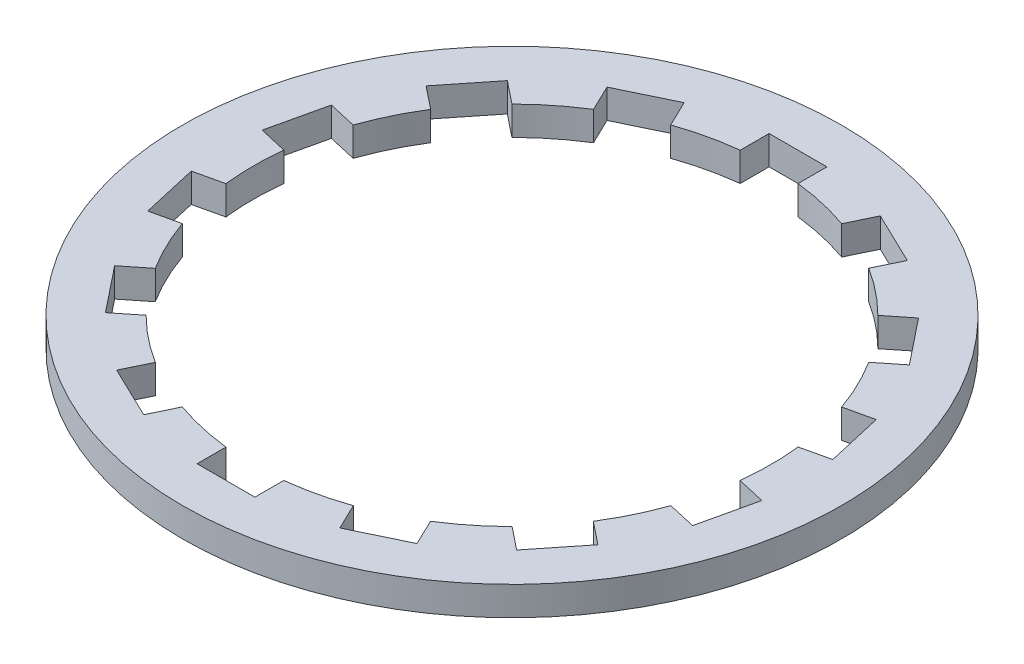
SolidWorks part; units mm, degrees
material "PET"
ref_plane "Front Plane" through (0, 0, 0) normal (0, 0, 1) x (1, 0, 0)
ref_plane "Top Plane" through (0, 0, 0) normal (0, 1, 0) x (1, 0, 0)
ref_plane "Right Plane" through (0, 0, 0) normal (1, 0, 0) x (0, 0, -1)
sketch "Sketch1" plane through (0, 0, 0) normal (0, 1, 0) x (1, 0, 0)
  line L0 (16.9593, 46.7402) -> (25.969, 42.4013)
  line L1 (-5, 44.4698) -> (5, 44.4698)
  line L2 (-5, 44.4698) -> (-5, 49.4698)
  line L3 (-5, 49.4698) -> (5, 49.4698)
  line L4 (5, 44.4698) -> (5, 49.4698)
  line L5 (23.7996, 37.8965) -> (25.969, 42.4013)
  line L6 (14.7899, 42.2353) -> (23.7996, 37.8965)
  line L7 (14.7899, 42.2353) -> (16.9593, 46.7402)
  line L8 (35.5596, 34.7531) -> (41.7945, 26.9348)
  line L9 (37.8853, 23.8173) -> (41.7945, 26.9348)
  line L10 (31.6504, 31.6356) -> (37.8853, 23.8173)
  line L11 (31.6504, 31.6356) -> (35.5596, 34.7531)
  line L12 (47.1169, 15.8827) -> (49.3421, 6.1334)
  line L13 (44.4674, 5.0208) -> (49.3421, 6.1334)
  line L14 (42.2422, 14.7701) -> (44.4674, 5.0208)
  line L15 (42.2422, 14.7701) -> (47.1169, 15.8827)
  line L16 (49.3421, -6.1334) -> (47.1169, -15.8827)
  line L17 (42.2422, -14.7701) -> (47.1169, -15.8827)
  line L18 (44.4674, -5.0208) -> (42.2422, -14.7701)
  line L19 (44.4674, -5.0208) -> (49.3421, -6.1334)
  line L20 (41.7945, -26.9348) -> (35.5596, -34.7531)
  line L21 (31.6504, -31.6356) -> (35.5596, -34.7531)
  line L22 (37.8853, -23.8173) -> (31.6504, -31.6356)
  line L23 (37.8853, -23.8173) -> (41.7945, -26.9348)
  line L24 (25.969, -42.4013) -> (16.9593, -46.7402)
  line L25 (14.7899, -42.2353) -> (16.9593, -46.7402)
  line L26 (23.7996, -37.8965) -> (14.7899, -42.2353)
  line L27 (23.7996, -37.8965) -> (25.969, -42.4013)
  line L28 (5, -49.4698) -> (-5, -49.4698)
  line L29 (-5, -44.4698) -> (-5, -49.4698)
  line L30 (5, -44.4698) -> (-5, -44.4698)
  line L31 (5, -44.4698) -> (5, -49.4698)
  line L32 (-16.9593, -46.7402) -> (-25.969, -42.4013)
  line L33 (-23.7996, -37.8965) -> (-25.969, -42.4013)
  line L34 (-14.7899, -42.2353) -> (-23.7996, -37.8965)
  line L35 (-14.7899, -42.2353) -> (-16.9593, -46.7402)
  line L36 (-35.5596, -34.7531) -> (-41.7945, -26.9348)
  line L37 (-37.8853, -23.8173) -> (-41.7945, -26.9348)
  line L38 (-31.6504, -31.6356) -> (-37.8853, -23.8173)
  line L39 (-31.6504, -31.6356) -> (-35.5596, -34.7531)
  line L40 (-47.1169, -15.8827) -> (-49.3421, -6.1334)
  line L41 (-44.4674, -5.0208) -> (-49.3421, -6.1334)
  line L42 (-42.2422, -14.7701) -> (-44.4674, -5.0208)
  line L43 (-42.2422, -14.7701) -> (-47.1169, -15.8827)
  line L44 (-49.3421, 6.1334) -> (-47.1169, 15.8827)
  line L45 (-42.2422, 14.7701) -> (-47.1169, 15.8827)
  line L46 (-44.4674, 5.0208) -> (-42.2422, 14.7701)
  line L47 (-44.4674, 5.0208) -> (-49.3421, 6.1334)
  line L48 (-41.7945, 26.9348) -> (-35.5596, 34.7531)
  line L49 (-31.6504, 31.6356) -> (-35.5596, 34.7531)
  line L50 (-37.8853, 23.8173) -> (-31.6504, 31.6356)
  line L51 (-37.8853, 23.8173) -> (-41.7945, 26.9348)
  line L52 (-25.969, 42.4013) -> (-16.9593, 46.7402)
  line L53 (-14.7899, 42.2353) -> (-16.9593, 46.7402)
  line L54 (-23.7996, 37.8965) -> (-14.7899, 42.2353)
  line L55 (-23.7996, 37.8965) -> (-25.969, 42.4013)
  circle A0 centre (0, 0) radius 44.75
  circle A1 centre (0, 0) radius 57
  point P63 (0, 0)
  dimension "D1" = 89.5
  dimension "D2" = 114
  dimension "D3" = 10
  dimension "D4" = 5
  dimension "D5" = 14
extrude "Boss-Extrude1" add sketch "Sketch1" along normal mid plane 5 contours A1 A0 L31 L28 L29 L35 L32 L33 L39 L36 L37 L43 L40 L41 L47 L44 L45 L51 L48 L49 L55 L52 L53 L2 L3 L4 L7 L0 L5 L11 L8 L9 L15 L12 L13 L19 L16 L17
